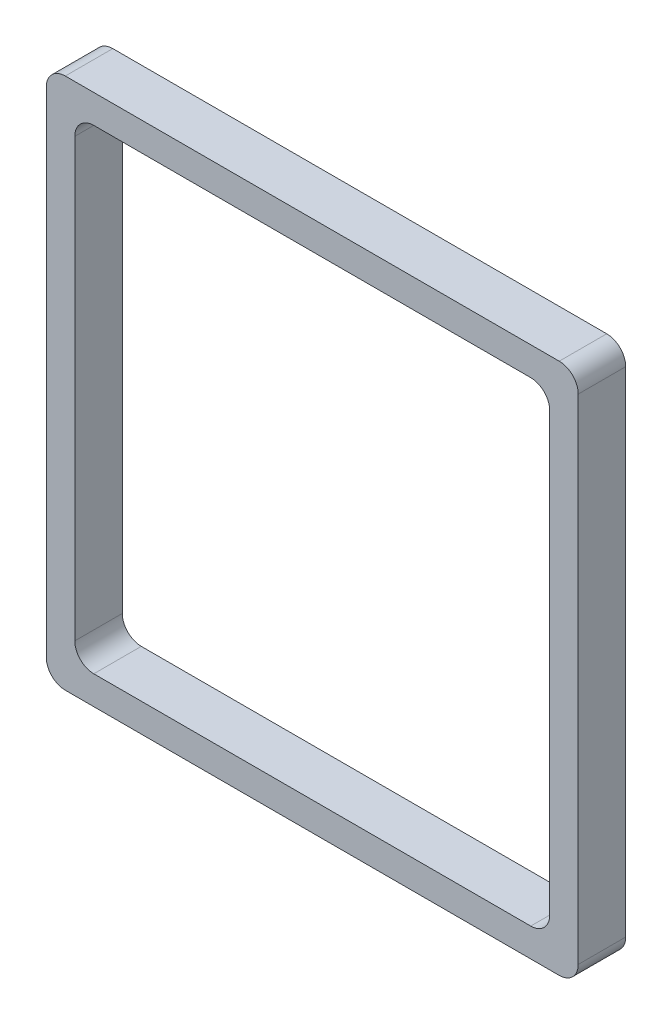
SolidWorks part; units mm, degrees
ref_plane "Спереди" through (0, 0, 0) normal (0, 0, 1) x (1, 0, 0)
ref_plane "Сверху" through (0, 0, 0) normal (0, 1, 0) x (1, 0, 0)
ref_plane "Справа" through (0, 0, 0) normal (1, 0, 0) x (0, 0, -1)
sketch "Эскиз1" plane through (0, 0, 0) normal (0, 0, 1) x (1, 0, 0)
  line L1 (26, -28) -> (-26, -28)
  line L2 (28, -26) -> (28, 26)
  line L3 (26, 28) -> (-26, 28)
  line L4 (-28, -26) -> (-28, 26)
  line L5 (23, -25) -> (-23, -25)
  line L6 (25, -23) -> (25, 23)
  line L7 (23, 25) -> (-23, 25)
  line L8 (-25, -23) -> (-25, 23)
  arc A0 (26, 28) -> (28, 26) centre (26, 26) cw
  arc A1 (-28, 26) -> (-26, 28) centre (-26, 26) cw
  arc A2 (-26, -28) -> (-28, -26) centre (-26, -26) cw
  arc A3 (28, -26) -> (26, -28) centre (26, -26) cw
  arc A4 (25, -23) -> (23, -25) centre (23, -23) cw
  arc A5 (23, 25) -> (25, 23) centre (23, 23) cw
  arc A6 (-23, 25) -> (-25, 23) centre (-23, 23) ccw
  arc A7 (-23, -25) -> (-25, -23) centre (-23, -23) cw
  point P0 (0, 0)
  point P6 (0, 0)
  point P7 (0, 0)
  point P8 (0, 25)
  point P9 (-25, 0)
  point P10 (-28, 0)
  point P13 (-15.4119, 35)
  point P14 (28, 28)
  point P17 (-28, 28)
  point P20 (-28, -28)
  point P35 (0, 28)
  dimension "D5" = 2
  dimension "D6" = 2
  dimension "D7" = 2
  dimension "D8" = 2
  dimension "D9" = 2
  dimension "D1" = 56
  dimension "D2" = 56
extrude "Бобышка-Вытянуть1" add sketch "Эскиз1" along normal blind 5
